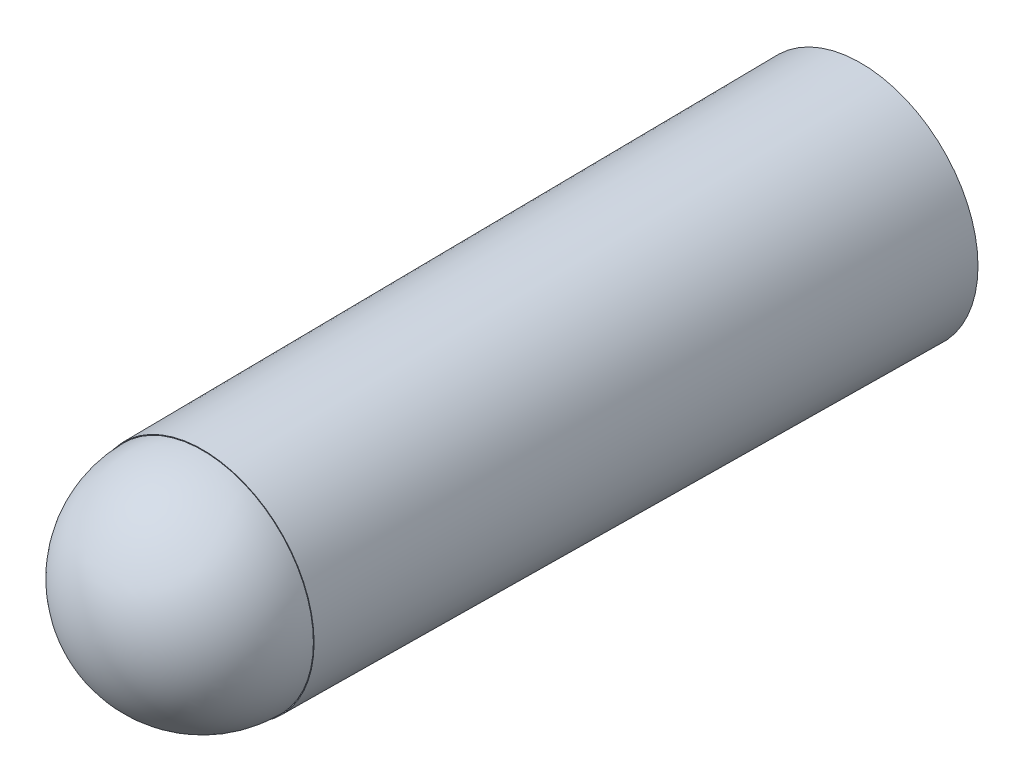
SolidWorks part; units mm, degrees
ref_plane "Front Plane" through (0, 0, 0) normal (0, 0, 1) x (1, 0, 0)
ref_plane "Top Plane" through (0, 0, 0) normal (0, 1, 0) x (1, 0, 0)
ref_plane "Right Plane" through (0, 0, 0) normal (1, 0, 0) x (0, 0, -1)
sketch "Sketch1" plane through (0, 0, 0) normal (0, 0, 1) x (1, 0, 0)
  circle A0 centre (0, 0) radius 44.55
  dimension "D1" = 89.1
extrude "Boss-Extrude1" add sketch "Sketch1" along normal blind 250 draft 0.5
sketch "Sketch2" plane through (0, 0, 0) normal (0, 0, -1) x (-1, 0, 0)
  line L0 (0, 39.55) -> (0, -39.55)
  arc A0 (0, -39.55) -> (0, 39.55) centre (0, 0) ccw
  dimension "D1" = 79.1
revolve "Cut-Revolve1" cut sketch "Sketch2" angle 360 about L0
sketch "Sketch3" plane through (0, 0, 250) normal (0, 0, 1) x (1, 0, 0)
  line L0 (0, 42.1065) -> (0, -42.1065)
  arc A0 (0, 42.1065) -> (0, -42.1065) centre (0, 0) ccw
revolve "Revolve1" add sketch "Sketch3" angle 360 about L0
